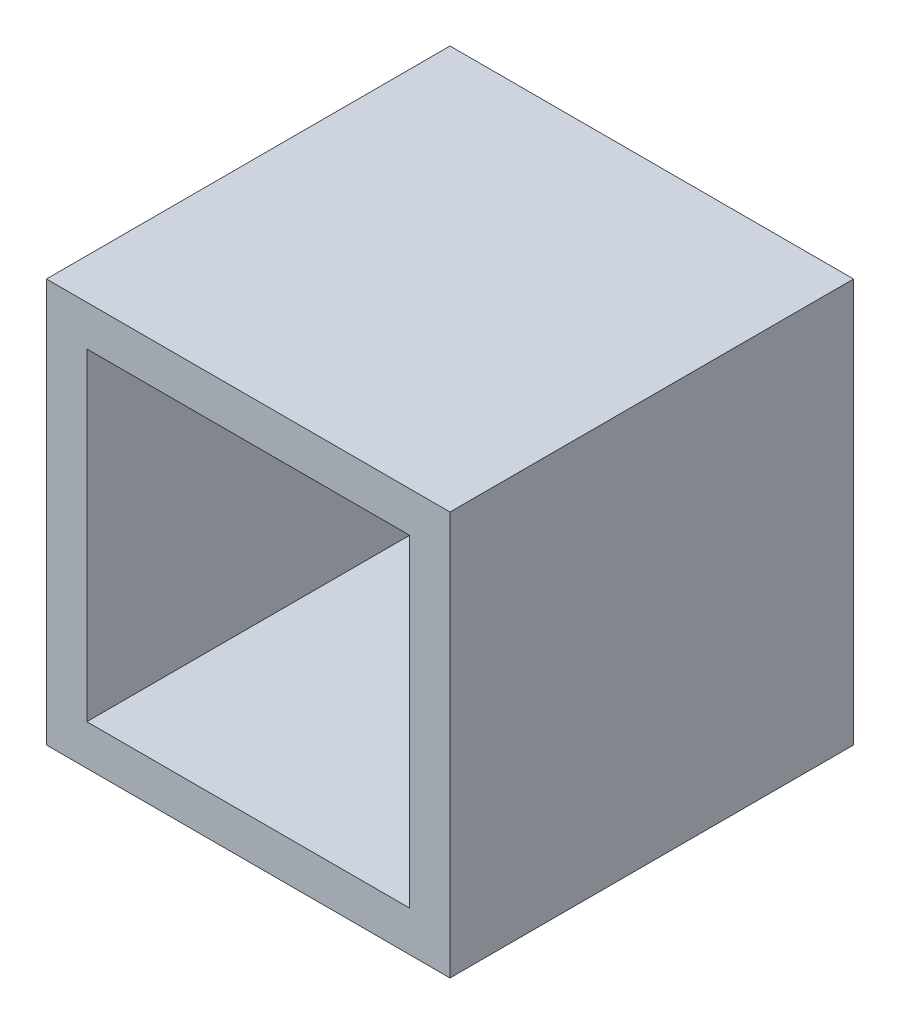
SolidWorks part; units mm, degrees
ref_plane "Front Plane" through (0, 0, 0) normal (0, 0, 1) x (1, 0, 0)
ref_plane "Top Plane" through (0, 0, 0) normal (0, 1, 0) x (1, 0, 0)
ref_plane "Right Plane" through (0, 0, 0) normal (1, 0, 0) x (0, 0, -1)
sketch "Sketch1" plane through (0, 0, 0) normal (0, 0, 1) x (1, 0, 0)
  line L1 (0, 0) -> (10, 0)
  line L2 (0, 0) -> (0, 10)
  line L3 (0, 10) -> (10, 10)
  line L4 (10, 0) -> (10, 10)
extrude "Boss-Extrude1" add sketch "Sketch1" along normal blind 10
shell "Shell1" thickness 1
